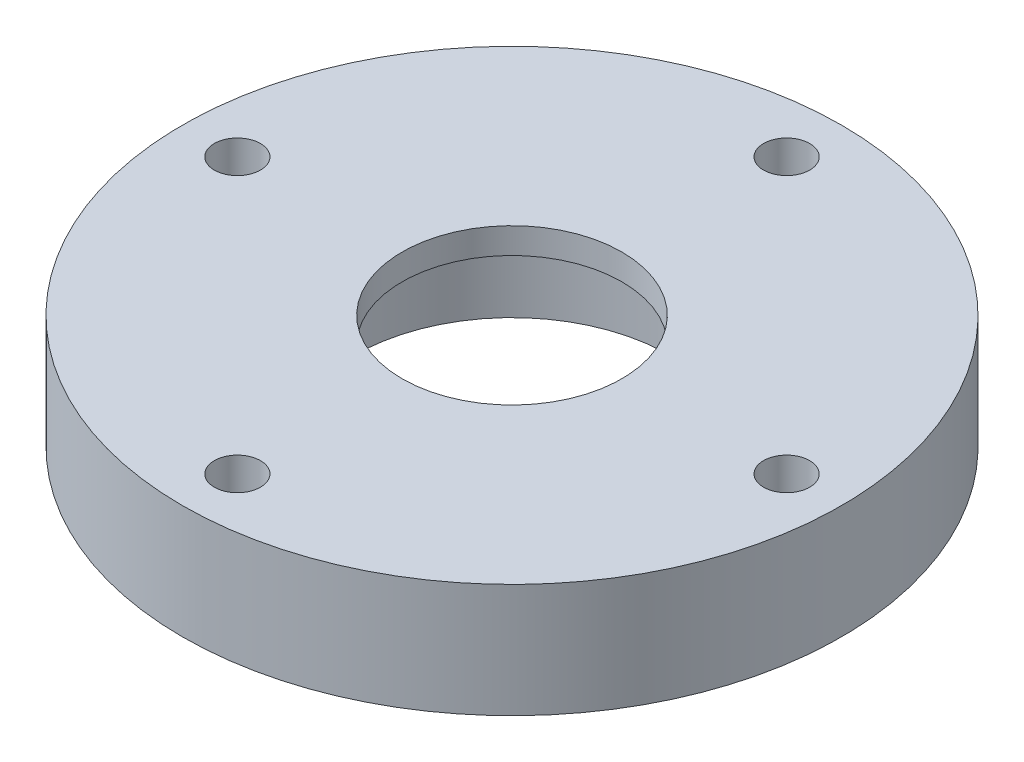
SolidWorks part; units mm, degrees
ref_plane "Front Plane" through (0, 0, 0) normal (0, 0, 1) x (1, 0, 0)
ref_plane "Top Plane" through (0, 0, 0) normal (0, 1, 0) x (1, 0, 0)
ref_plane "Right Plane" through (0, 0, 0) normal (1, 0, 0) x (0, 0, -1)
sketch "Sketch1" plane through (0, 0, 0) normal (0, 1, 0) x (1, 0, 0)
  circle A0 centre (0, 0) radius 10
  circle A1 centre (0, 0) radius 25 construction
  circle A2 centre (0, 0) radius 30
  circle A3 centre (0, 25) radius 2.1
  circle A4 centre (25, 0) radius 2.1
  circle A5 centre (0, -25) radius 2.1
  circle A6 centre (-25, 0) radius 2.1
  dimension "D1" = 4.2
  dimension "D2" = 60
  dimension "D3" = 50
  dimension "D4" = 20
extrude "Boss-Extrude1" add sketch "Sketch1" along normal blind 10.35
sketch "Sketch2" plane through (0, 0, 0) normal (0, 1, 0) x (1, 0, 0)
  circle A0 centre (0, 0) radius 14.3875
  dimension "D1" = 28.775
extrude "Cut-Extrude2" cut sketch "Sketch2" along normal blind 8
